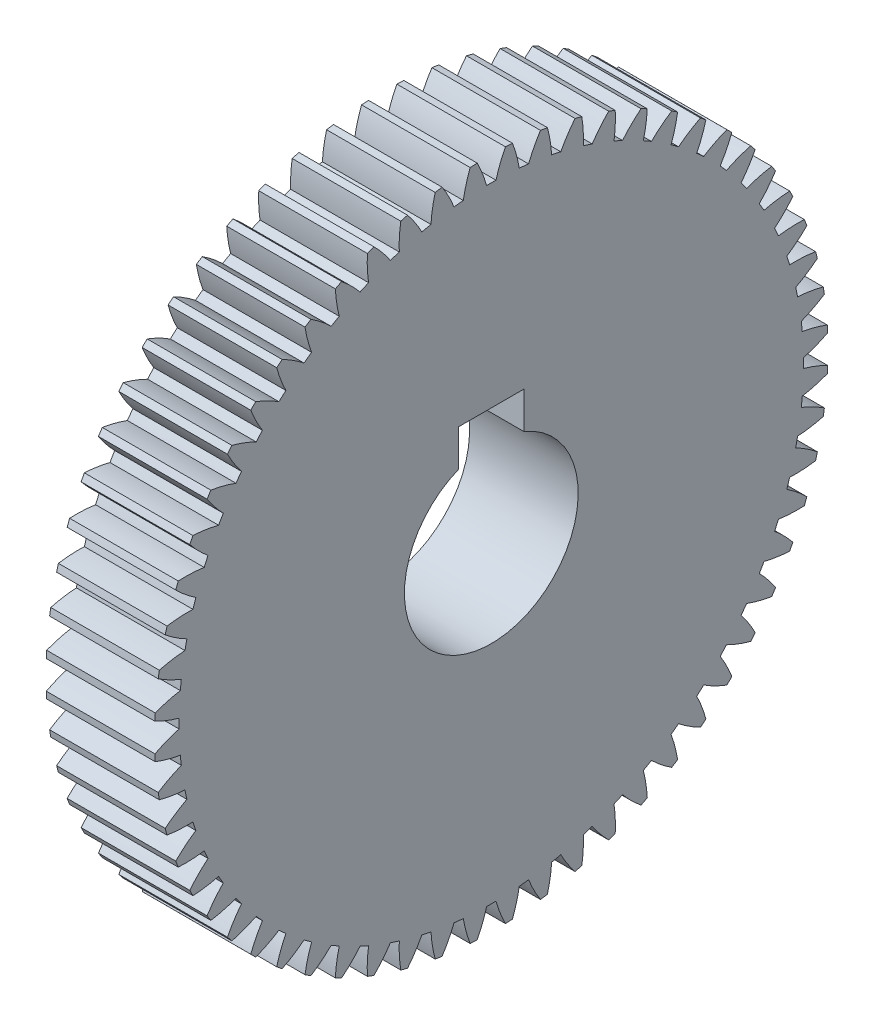
SolidWorks part; units mm, degrees
ref_plane "Plane1" through (0, 0, 0) normal (0, 0, 1) x (1, 0, 0)
ref_plane "Plane2" through (0, 0, 0) normal (0, 1, 0) x (1, 0, 0)
ref_plane "Plane3" through (0, 0, 0) normal (1, 0, 0) x (0, 0, -1)
other "Configuration Table"
sketch "HoldingSke" plane through (0, 0, 0) normal (0, 1, 0) x (1, 0, 0)
  line L0 (0, 0) -> (1, -1.7321)
  line L1 (-15, 0) -> (100, 0) construction
  line L2 (0, 0) -> (-2.1039, 2.3779)
  line L3 (0, 0) -> (-11.863, 4.5341)
  line L4 (0, 0) -> (4.318, 7.479)
  line L5 (0, 0) -> (-46.8476, -17.4728)
  line L6 (0, 0) -> (-4.1448, -2.7965)
  line L7 (-2.1039, 2.3779) -> (8.6586, 51.2059)
  line L8 (-76.2, 54.61) -> (-74.8, 54.61)
  line L9 (-71.009, 38.7566) -> (-53.1078, 45.2721)
  line L10 (-76.2, 71.12) -> (104.1128, 71.12)
  line L11 (0, 0) -> (-5, 0)
  line L12 (-76.2, 101.6) -> (-76.181, 101.6)
  line L13 (24.9733, 27.94) -> (52.9518, 28.4284)
  line L14 (24.9733, 27.94) -> (24.9743, 27.94)
  line L15 (24.9733, 27.94) -> (100.4006, 29.5858)
  line L16 (-63.627, -0.5) -> (-12.827, -0.5)
  circle A0 centre (0, 0) radius 4
  circle A1 centre (0, 0) radius 14.374
  circle A2 centre (0, 0) radius 37.5
  circle A3 centre (0, 0) radius 4
  dimension "MHD" = 28.748
  dimension "Hub_dia" = 75
  dimension "Bore" = 8
  dimension "MBD" = 8
  dimension "Num_teeth" = 60
  dimension "Pitch" = 2
  dimension "Overall_len" = 50
  dimension "Show_teeth" = 60
  dimension "Thickness" = 5
  dimension "OAL" = 50.0001
  dimension "T_dim" = 1.4
  dimension "Ap" = 20
  dimension "H" = 19.05
  dimension "Pitch_radius" = 180.3128
  dimension "Width" = 5
  dimension "Backlash" = 0.019
  dimension "Addendum_fac" = 1
  dimension "Dedendum_fac" = 1.25
  dimension "Clearance_fac" = 0.25
  dimension "Dedendum_add" = 0.001
  dimension "Module" = 0.5
sketch "BasProSke" plane through (0, 0, 0) normal (0, 1, 0) x (1, 0, 0)
  line L0 (-10, 0) -> (60, 0) construction
  line L1 (0, 0) -> (0, 15.5)
  line L2 (0, 0) -> (5, 0)
  line L3 (5, 0) -> (5, 15.5)
  line L4 (5, 15.5) -> (0, 15.5)
  dimension "Thickness" = 5
  dimension "Diameter" = 31
revolve "Base-Revolve" add sketch "BasProSke" angle 360 about L0
sketch "TooCutSke" plane through (0, 0, 0) normal (1, 0, 0) x (0, 0, -1)
  line L1 (0, 0) -> (0, 107) construction
  line L2 (0, 0) -> (-0.4259, 14.994) construction
  line L3 (0, 0) -> (-1.5696, 29.9503) construction
  line L4 (-0.4259, 14.994) -> (-0.7848, 14.9751) construction
  arc A0 (0.2149, 14.3724) -> (-0.2149, 14.3724) centre (0, 0) ccw
  arc A1 (0.6627, 15.5112) -> (-0.6627, 15.5112) centre (0, 0) ccw
  circle A2 centre (0, 0) radius 15 construction
  circle A3 centre (0, 0) radius 14.0954 construction
  arc A4 (-0.2149, 14.3724) -> (-0.6627, 15.5112) centre (-5.9936, 12.7576) ccw
  arc A5 (0.6627, 15.5112) -> (0.2149, 14.3724) centre (5.9936, 12.7576) ccw
  dimension "Root_dia" = 28.748
  dimension "Overcut_dia" = 31.0508
  dimension "Pitch_dia" = 30
  dimension "Base_dia" = 28.1908
  dimension "Flank_rad" = 6
  dimension "Half_ang" = 3
  dimension "Half_CT" = 0.3594
extrude "ToothCut" cut sketch "TooCutSke" along normal through all
fillet "Breaks" [suppressed] radius 0.01
fillet "RootFillets" [suppressed] radius 0.126
pattern_circular "TeethCuts" count 60 every 6 about axis through (-10, 0, 0) along (1, 0, 0) of "ToothCut", "RootFillets", "Breaks"
sketch "HubNeaOneSke" plane through (0, 0, 0) normal (-1, 0, 0) x (0, 0, 1)
  circle A0 centre (0, 0) radius 14.374
  dimension "Diameter" = 28.748
extrude "HubNearOne" [suppressed] add sketch "HubNeaOneSke" along normal blind 45.0001
sketch "HubNeaBotSke" plane through (0, 0, 0) normal (-1, 0, 0) x (0, 0, 1)
  circle A0 centre (0, 0) radius 14.374
  dimension "Diameter" = 28.748
extrude "HubNearBoth" [suppressed] add sketch "HubNeaBotSke" along normal blind 22.5
ref_plane "FarPln" through (5, 0, 0) normal (1, 0, 0) x (0, 0, -1)
sketch "HubFarSke" plane through (5, 0, 0) normal (1, 0, 0) x (0, 0, -1)
  circle A0 centre (0, 0) radius 14.374
  dimension "Diameter" = 28.748
extrude "HubFar" [suppressed] add sketch "HubFarSke" along normal blind 22.5
sketch "BorSke" plane through (0, 0, 0) normal (1, 0, 0) x (0, 0, -1)
  circle A0 centre (0, 0) radius 4
  dimension "Diameter" = 8
extrude "Bore" cut sketch "BorSke" along normal mid plane 100.0001
sketch "KeySke" plane through (0, 0, 0) normal (1, 0, 0) x (0, 0, -1)
  line L0 (-1.5, 0) -> (-1.5, 5.4)
  line L1 (-1.5, 5.4) -> (1.5, 5.4)
  line L2 (1.5, 5.4) -> (1.5, 0)
  line L3 (0, 0) -> (0, 34) construction
  line L4 (-1.5, 0) -> (1.5, 0)
  dimension "Offset" = 5.4
  dimension "Width" = 3
extrude "Keyway" cut sketch "KeySke" along normal mid plane 100.0001
pattern_circular "Keyway2" [suppressed] count 2 every 90 about axis through (-10, 0, 0) along (1, 0, 0)
equation "' \"Module@HoldingSke\" = 6.35"
equation "' \"Num_teeth@HoldingSke\" = 12"
equation "' \"Ap@HoldingSke\" =  20"
equation "' \"Ap@HoldingSke\" = 20"
equation "' \"Width@HoldingSke\" = 0.5 * 25.4"
equation "' \"Hub_dia@HoldingSke\"= 1 * 25.4"
equation "' \"Hub_dia@HoldingSke\" = 1 * 25.4"
equation "' \"Overall_len@HoldingSke\" = 1.0 * 25.4"
equation "' \"Bore@HoldingSke\" = 0.75 * 25.4"
equation "' \"T_dim@HoldingSke\" = 0.1 * 25.4"
equation "' \"Width@KeySke\" = 0.25 * 25.4"
equation "' \"Show_teeth@HoldingSke\" = 13"
equation "' \"Backlash@HoldingSke\" = 0.009 * 25.4"
equation "' \"Addendum_fac@HoldingSke\" = 1.0"
equation "' \"Dedendum_fac@HoldingSke\" = 1.25"
equation "' \"Dedendum_add@HoldingSke\" = 0.00005 * 25.4"
equation "' \"Clearance_fac@HoldingSke\" = 0.25"
equation "\"Pitch@HoldingSke\" = 1 / \"Module@HoldingSke\""
equation "\"Overcut_dia@TooCutSke\" = (\"Num_teeth@HoldingSke\" + 2 * \"Addendum_fac@HoldingSke\") / \"Pitch@HoldingSke\" + 0.002 * 25.4"
equation "\"Pitch_dia@TooCutSke\" = \"Num_teeth@HoldingSke\" / \"Pitch@HoldingSke\""
equation "\"Base_dia@TooCutSke\" = \"Num_teeth@HoldingSke\" / \"Pitch@HoldingSke\" * cos((\"Ap@HoldingSke\"  * 3.14159265 / 180))"
equation "\"Root_dia@TooCutSke\" = (\"Num_teeth@HoldingSke\" + 2) / \"Pitch@HoldingSke\" - 2 * (\"Addendum_fac@HoldingSke\" + \"Dedendum_fac@HoldingSke\") / \"Pitch@HoldingSke\" - \"Dedendum_add@HoldingSke\" * 2"
equation "\"Half_ang@TooCutSke\" = 180 / \"Num_teeth@HoldingSke\""
equation "\"Half_CT@TooCutSke\" = \"Num_teeth@HoldingSke\" / \"Pitch@HoldingSke\" * sin((3.14159265 / 2 / \"Num_teeth@HoldingSke\")) / 2 - 7 * \"Backlash@HoldingSke\" / 4"
equation "\"Flank_rad@TooCutSke\" = \"Num_teeth@HoldingSke\" / \"Pitch@HoldingSke\" / 5"
equation "\"Radius@RootFillets\" = \"Clearance_fac@HoldingSke\" / \"Pitch@HoldingSke\" + \"Dedendum_add@HoldingSke\""
equation "\"Break_rad@Breaks\" = 0.02 / \"Pitch@HoldingSke\""
equation "\"Thickness@HoldingSke\" = \"Width@HoldingSke\""
equation "\"OAL@HoldingSke\" = \"Thickness@HoldingSke\""
equation "\"MHD@HoldingSke\" = (\"Num_teeth@HoldingSke\" + 2) / \"Pitch@HoldingSke\" - 2 * (\"Addendum_fac@HoldingSke\" + \"Dedendum_fac@HoldingSke\")  / \"Pitch@HoldingSke\" - \"Dedendum_add@HoldingSke\" * 2"
equation "\"MBD@HoldingSke\" = (\"Num_teeth@HoldingSke\" + 2) / \"Pitch@HoldingSke\" - 2 * (\"Addendum_fac@HoldingSke\" + \"Dedendum_fac@HoldingSke\")  / \"Pitch@HoldingSke\" - \"Dedendum_add@HoldingSke\" * 2 - 0.002 * 25.4"
equation "\"MHD@HoldingSke\" = ((sgn( \"MHD@HoldingSke\" - \"Hub_dia@HoldingSke\" )-1)*( \"MHD@HoldingSke\" - \"Hub_dia@HoldingSke\" ))/-2+ \"Hub_dia@HoldingSke\""
equation "\"MBD@HoldingSke\" = ((sgn( \"MBD@HoldingSke\" - \"Bore@HoldingSke\" )-1)*( \"MBD@HoldingSke\" - \"Bore@HoldingSke\" ))/-2+ \"Bore@HoldingSke\""
equation "\"OAL@HoldingSke\" = ((sgn( \"OAL@HoldingSke\" - \"Overall_len@HoldingSke\" )+1)*( \"OAL@HoldingSke\" - \"Overall_len@HoldingSke\" ))/2 + \"Overall_len@HoldingSke\" + 0.000002 * 25.4"
equation "\"Num_teeth@TeethCuts\" = int( \"Show_teeth@HoldingSke\" ) + 1"
equation "\"Num_teeth@TeethCuts\" = ((sgn( \"Num_teeth@TeethCuts\" - \"Num_teeth@HoldingSke\" )-1)*( \"Num_teeth@TeethCuts\" - \"Num_teeth@HoldingSke\" ))/-2+ \"Num_teeth@HoldingSke\""
equation "\"Num_teeth@TeethCuts\" = ((sgn( \"Num_teeth@TeethCuts\" - 2.0)+1)*( \"Num_teeth@TeethCuts\" - 2.0))/2 +2.0"
equation "\"Angle@TeethCuts\" = 360.0 / \"Num_teeth@HoldingSke\""
equation "\"Diameter@BasProSke\" = (\"Num_teeth@HoldingSke\" + 2 * \"Addendum_fac@HoldingSke\") / \"Pitch@HoldingSke\""
equation "\"Thickness@BasProSke\"  = \"Thickness@HoldingSke\""
equation "' \"Fillet_rad@BasProSke\" =  \"Thickness@HoldingSke\" * 0.05"
equation "' \"Fillet_rad@BasProSke\" = \"Thickness@HoldingSke\" * 0.05"
equation "\"MHD@HoldingSke\" = ((sgn( \"MHD@HoldingSke\" - \"Root_dia@TooCutSke\" )-1)*( \"MHD@HoldingSke\" - \"Root_dia@TooCutSke\" ))/-2+ \"Root_dia@TooCutSke\""
equation "\"Diameter@HubNeaOneSke\" = \"MHD@HoldingSke\""
equation "\"Length@HubNearOne\" = \"OAL@HoldingSke\" - \"Thickness@BasProSke\""
equation "\"Diameter@HubNeaBotSke\" = \"MHD@HoldingSke\""
equation "\"Length@HubNearBoth\" = ( \"OAL@HoldingSke\" - \"Thickness@BasProSke\" ) / 2.0"
equation "\"Thickness@FarPln\" = \"Thickness@BasProSke\""
equation "\"Diameter@HubFarSke\" = \"MHD@HoldingSke\""
equation "\"Length@HubFar\" = ( \"OAL@HoldingSke\" - \"Thickness@BasProSke\" ) / 2.0"
equation "\"Diameter@BorSke\" = \"MBD@HoldingSke\""
equation "\"D1@Bore\" = \"OAL@HoldingSke\" * 2.0"
equation "\"D1@Keyway\" = \"OAL@HoldingSke\" * 2.0"
equation "\"Offset@KeySke\" = \"T_dim@HoldingSke\" + \"MBD@HoldingSke\" / 2.0"
